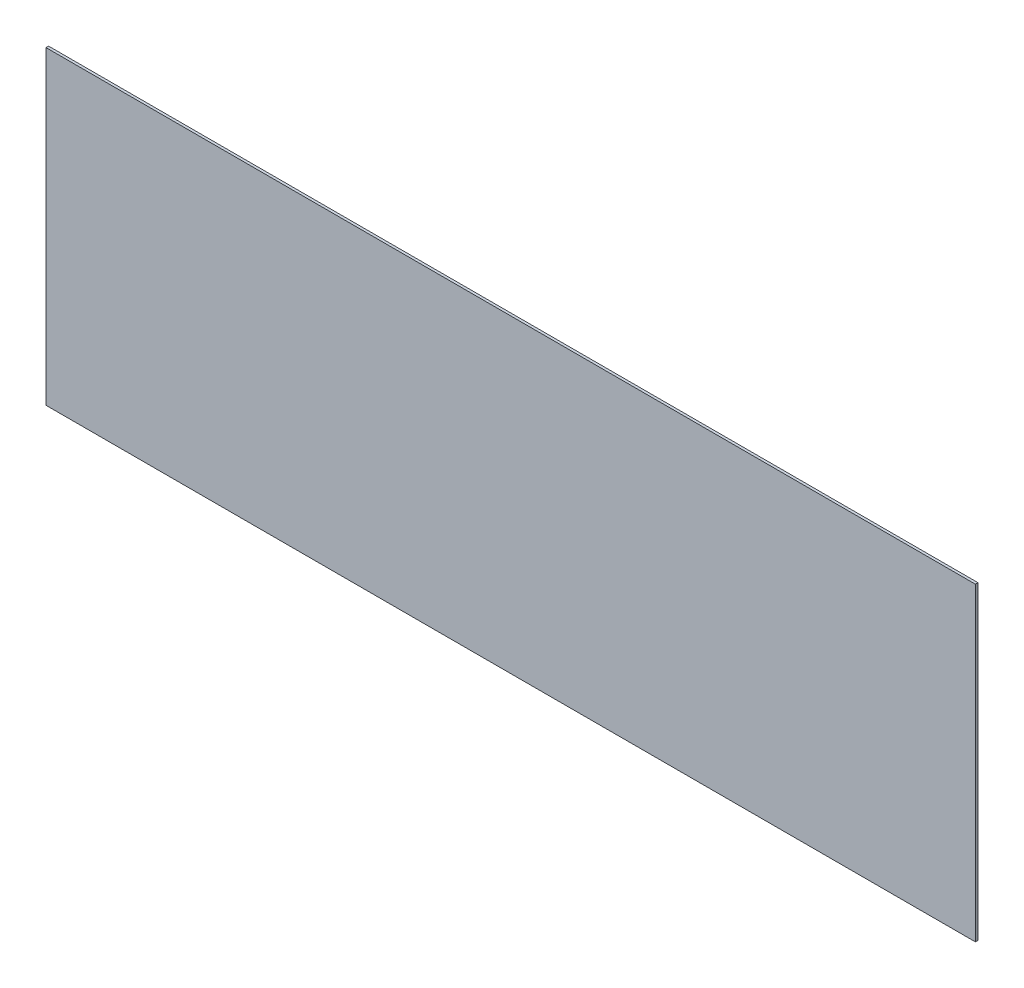
SolidWorks part; units mm, degrees
ref_plane "Front Plane" through (0, 0, 0) normal (0, 0, 1) x (1, 0, 0)
ref_plane "Top Plane" through (0, 0, 0) normal (0, 1, 0) x (1, 0, 0)
ref_plane "Right Plane" through (0, 0, 0) normal (1, 0, 0) x (0, 0, -1)
sketch "Sketch1" plane through (0, 0, 0) normal (0, 0, 1) x (1, 0, 0)
  line L1 (-900, 300) -> (900, 300)
  line L2 (-900, 300) -> (-900, -300)
  line L3 (-900, -300) -> (900, -300)
  line L4 (900, 300) -> (900, -300)
  line L5 (-900, 300) -> (900, -300) construction
  line L6 (-900, -300) -> (900, 300) construction
  point P0 (0, 0)
  dimension "D1" = 1800
  dimension "D2" = 600
extrude "Boss-Extrude1" add sketch "Sketch1" along normal blind 5
